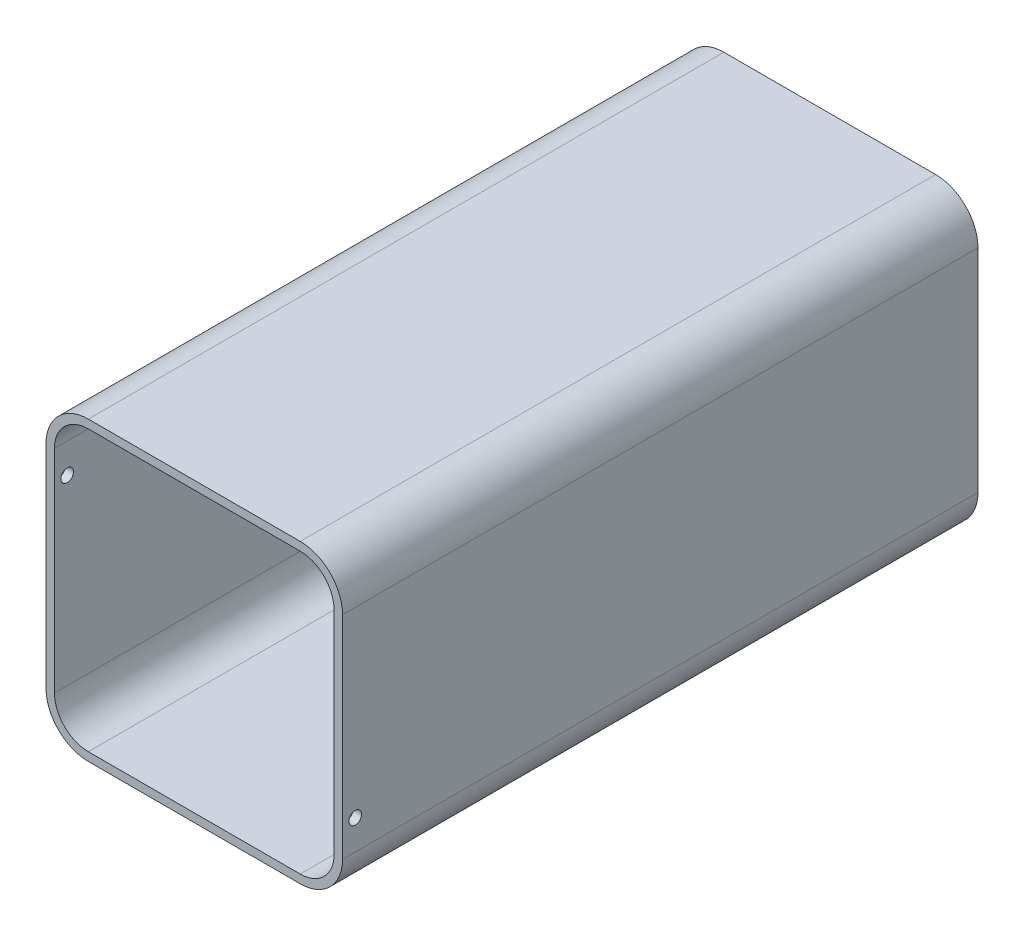
SolidWorks part; units mm, degrees
ref_plane "前视基准面" through (0, 0, 0) normal (0, 0, 1) x (1, 0, 0)
ref_plane "上视基准面" through (0, 0, 0) normal (0, 1, 0) x (1, 0, 0)
ref_plane "右视基准面" through (0, 0, 0) normal (1, 0, 0) x (0, 0, -1)
sketch "草图1" plane through (0, 0, 0) normal (0, 0, 1) x (1, 0, 0)
  line L0 (-28.3182, 20.4135) -> (-28.3182, -29.5865)
  line L1 (-18.3182, -39.5865) -> (31.6818, -39.5865)
  line L2 (41.6818, -29.5865) -> (41.6818, 20.4135)
  line L3 (31.6818, 30.4135) -> (-18.3182, 30.4135)
  arc A0 (41.6818, 20.4135) -> (31.6818, 30.4135) centre (31.6818, 20.4135) ccw
  arc A1 (31.6818, -39.5865) -> (41.6818, -29.5865) centre (31.6818, -29.5865) ccw
  arc A2 (-18.3182, -39.5865) -> (-28.3182, -29.5865) centre (-18.3182, -29.5865) cw
  arc A3 (-18.3182, 30.4135) -> (-28.3182, 20.4135) centre (-18.3182, 20.4135) ccw
  dimension "D1" = 10
  dimension "D2" = 70
  dimension "D3" = 70
extrude "凸台-拉伸1" add sketch "草图1" along normal blind 150
shell "抽壳1" thickness 2
sketch "草图2" plane through (0, 0, 0) normal (0, 0, -1) x (-1, 0, 0)
  line L0 (28.3182, -4.5865) -> (-46.3898, -4.5865) construction
  line L1 (28.3182, 20.4135) -> (28.3182, -29.5865) construction
  line L2 (-6.6818, 30.4135) -> (-6.6818, -48.7763) construction
  line L3 (-31.6818, 30.4135) -> (18.3182, 30.4135) construction
  line L4 (0.5704, -25.8041) -> (0.5704, 16.6311)
  line L5 (0.5704, 16.6311) -> (21.5704, 16.6311)
  line L6 (21.5704, 16.6311) -> (21.5704, -25.8041)
  line L7 (11.0704, 16.6311) -> (11.0704, 27.6954) construction
  line L8 (0.5704, -25.8041) -> (21.5704, -25.8041)
  line L9 (16.0704, 20.1235) -> (11.0704, 20.1235) construction
  circle A0 centre (16.0704, 20.1235) radius 1.7
  circle A1 centre (6.0704, 20.1235) radius 1.7
  circle A2 centre (16.0704, -29.2965) radius 1.7
  circle A3 centre (6.0704, -29.2965) radius 1.7
  point P24 (0.5704, -4.5865)
  point P25 (21.5704, -4.5865)
  dimension "D1" = 49.42
extrude "切除-拉伸1" cut sketch "草图2" against normal blind 150
sketch "草图3" plane through (0, 0, 0) normal (0, 0, -1) x (-1, 0, 0)
  line L1 (-15.6247, 9.6062) -> (-27.5319, 9.6062)
  line L2 (-15.6247, 9.6062) -> (-15.6247, -20.1429)
  line L3 (-15.6247, -20.1429) -> (-27.5319, -20.1429)
  line L4 (-27.5319, 9.6062) -> (-27.5319, -20.1429)
extrude "切除-拉伸2" cut sketch "草图3" against normal blind 10
fillet "圆角1" radius 2 1 edges at (15.6247, 9.6062, 1)
fillet "圆角2" radius 2 1 edges at (15.6247, -20.1429, 1)
fillet "圆角3" radius 2 1 edges at (27.5319, -20.1429, 1)
fillet "圆角4" radius 2 1 edges at (27.5319, 9.6062, 1)
sketch "草图4" plane through (39.6818, 0, 0) normal (-1, 0, 0) x (0, 0, 1)
  line L0 (150, -29.5865) -> (150, 20.4135) construction
  line L1 (150, -29.5865) -> (2, -29.5865) construction
  circle A0 centre (147, -22.5865) radius 1.5
  dimension "D1" = 3
  dimension "D2" = 7
extrude "切除-拉伸3" cut sketch "草图4" against normal blind 7
sketch "草图5" plane through (-26.3182, 0, 0) normal (1, 0, 0) x (0, 0, -1)
  line L0 (-150, 20.4135) -> (-150, -29.5865) construction
  line L1 (-150, 20.4135) -> (-2, 20.4135) construction
  circle A0 centre (-147, 13.4135) radius 1.5
  dimension "D1" = 3
  dimension "D2" = 7
extrude "切除-拉伸4" cut sketch "草图5" against normal blind 7
